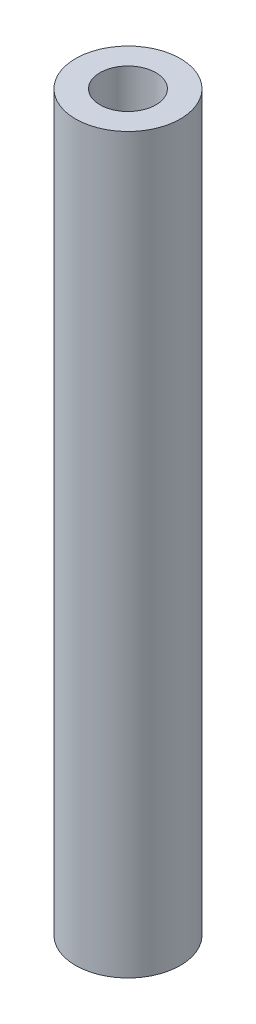
SolidWorks part; units mm, degrees
material "ABS"
ref_plane "Front Plane" through (0, 0, 0) normal (0, 0, 1) x (1, 0, 0)
ref_plane "Top Plane" through (0, 0, 0) normal (0, 1, 0) x (1, 0, 0)
ref_plane "Right Plane" through (0, 0, 0) normal (1, 0, 0) x (0, 0, -1)
sketch "Sketch1" plane through (0, 0, 0) normal (0, 1, 0) x (1, 0, 0)
  circle A0 centre (0, 0) radius 4.7625
  circle A1 centre (0, 0) radius 2.54
  dimension "D1" = 5.08
  dimension "D2" = 9.525
extrude "Boss-Extrude1" add sketch "Sketch1" along normal blind 66.675
